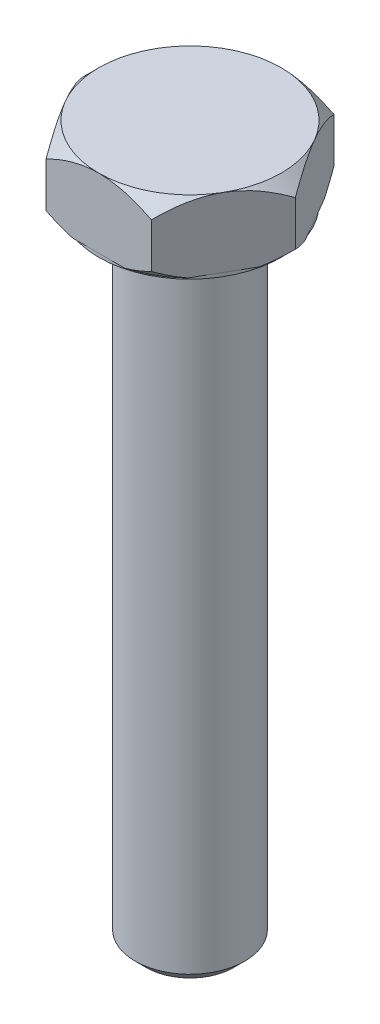
SolidWorks part; units mm, degrees
material "Cast Stainless Steel"
ref_plane "Front Plane" through (0, 0, 0) normal (0, 0, 1) x (1, 0, 0)
ref_plane "Top Plane" through (0, 0, 0) normal (0, 1, 0) x (1, 0, 0)
ref_plane "Right Plane" through (0, 0, 0) normal (1, 0, 0) x (0, 0, -1)
sketch "Sketch1" plane through (0, 0, 0) normal (0, 1, 0) x (1, 0, 0)
  line L0 (0, 0) -> (5.7735, 0) construction
  line L1 (5.7735, 0) -> (2.8868, 5)
  line L2 (2.8868, 5) -> (-2.8868, 5)
  line L3 (-2.8868, 5) -> (-5.7735, 0)
  line L4 (-5.7735, 0) -> (-2.8868, -5)
  line L5 (-2.8868, -5) -> (2.8868, -5)
  line L6 (2.8868, -5) -> (5.7735, 0)
  circle A0 centre (0, 0) radius 5 construction
  dimension "D1" = 10
extrude "Boss-Extrude1" add sketch "Sketch1" against normal blind 4
sketch "Sketch4" plane through (0, 0, 0) normal (1, 0, 0) x (0, 0, -1)
  line L0 (-5, 0) -> (-6, 0)
  line L1 (-6, 0) -> (-6, -1)
  line L2 (-6, -1) -> (-5, 0)
  line L3 (-5, -2) -> (5, -2) construction
  line L4 (-6, -3) -> (-5, -4)
  line L5 (-6, -4) -> (-6, -3)
  line L6 (-5, -4) -> (-6, -4)
  line L7 (0, 0) -> (0, -2) construction
  dimension "D1" = 45
  dimension "D2" = 2
  dimension "D3" = 1
  dimension "D4" = 10
revolve "Cut-Revolve1" cut sketch "Sketch4" angle 360 about L7
sketch "Sketch2" plane through (0, -4, 0) normal (0, -1, 0) x (1, 0, 0)
  circle A0 centre (0, 0) radius 5
  dimension "D1" = 10
extrude "Cut-Extrude1" cut sketch "Sketch2" against normal blind 0.2 flip side to cut
sketch "Sketch3" plane through (0, -4, 0) normal (0, -1, 0) x (1, 0, 0)
  circle A0 centre (0, 0) radius 3
  dimension "D1" = 6
extrude "Boss-Extrude2" add sketch "Sketch3" along normal blind 35
chamfer "Chamfer1" distance 0.6 angle 45 1 edges at (0, -39, -3)
equation "\"k\" = 4"
equation "\"e\" = 11.05"
equation "\"S\" = 10"
equation "\"L\"= 35"
equation "\"D1@Sketch1\"=\"S\""
equation "\"D1@Boss-Extrude1\"=\"k\""
equation "\"D1@Sketch2\"=\"S\""
equation "\"D1@Cut-Extrude1\"=\"k\"/20"
equation "\"d\"= 6"
equation "\"D1@Sketch3\"=\"d\""
equation "\"D1@Boss-Extrude2\"=\"L\""
equation "\"D2@Sketch4\"=\"k\"/2"
equation "\"D3@Sketch4\"=\"D2@Sketch4\"-1"
equation "\"D4@Sketch4\"=\"S\""
equation "\"D1@Chamfer1\"=\"d\"/10"
